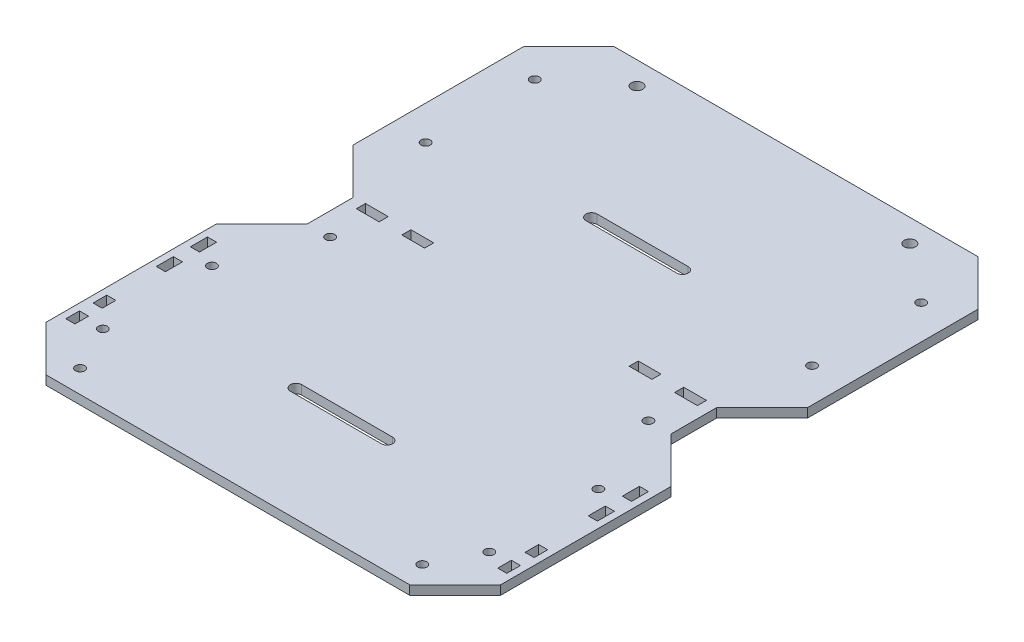
SolidWorks part; units mm, degrees
ref_plane "Front Plane" through (0, 0, 0) normal (0, 0, 1) x (1, 0, 0)
ref_plane "Top Plane" through (0, 0, 0) normal (0, 1, 0) x (1, 0, 0)
ref_plane "Right Plane" through (0, 0, 0) normal (1, 0, 0) x (0, 0, -1)
sketch "Sketch1" plane through (0, 0, 0) normal (0, 1, 0) x (1, 0, 0)
  line L0 (0, -190.8443) -> (0, 164.7825) construction
  line L1 (20, -75.5426) -> (-20, -75.5426) construction
  line L2 (20, -78.0426) -> (-20, -78.0426)
  line L3 (20, -73.0426) -> (-20, -73.0426)
  line L4 (-164.6479, -0.5426) -> (181.8685, -0.5426) construction
  line L5 (145.0227, -10.5426) -> (-122.4663, -10.5426) construction
  line L6 (-80, -10.5426) -> (-80, 9.4574)
  line L7 (-45, 9.4574) -> (-80, 9.4574) construction
  line L8 (20, 54.4574) -> (-20, 54.4574) construction
  line L9 (20, 56.9574) -> (-20, 56.9574)
  line L10 (20, 51.9574) -> (-20, 51.9574)
  line L15 (80, -10.5426) -> (80, 9.4574)
  line L17 (80, -125.5426) -> (-80, -125.5426)
  line L19 (100, -105.5426) -> (100, -30.5426)
  line L20 (100, -105.5426) -> (80, -125.5426)
  line L21 (80, -10.5426) -> (100, -30.5426)
  line L22 (-80, -10.5426) -> (-100, -30.5426)
  line L23 (-100, -105.5426) -> (-80, -125.5426)
  line L24 (-100, -105.5426) -> (-100, -30.5426)
  line L34 (80, 124.4574) -> (-80, 124.4574)
  line L36 (100, 104.4574) -> (80, 124.4574)
  line L37 (100, 104.4574) -> (100, 29.4574)
  line L39 (80, 9.4574) -> (100, 29.4574)
  line L42 (-80, 9.4574) -> (-100, 29.4574)
  line L44 (97, -37.5) -> (97, -45)
  line L45 (97, -93.8222) -> (97, -99.8222)
  line L46 (75, 10) -> (65, 10)
  line L47 (93, -45) -> (93, -37.5)
  line L48 (97, -52.5) -> (97, -60)
  line L49 (97, -37.5) -> (93, -37.5)
  line L50 (97, -45) -> (93, -45)
  line L51 (97, -99.8222) -> (93, -99.8222)
  line L52 (93, -52.5) -> (97, -52.5)
  line L53 (97, -60) -> (93, -60)
  line L54 (93, -99.8222) -> (93, -93.8222)
  line L55 (93, -93.8222) -> (97, -93.8222)
  line L56 (55, 6) -> (45, 6)
  line L57 (97, -87.8222) -> (93, -87.8222)
  line L58 (93, -87.8222) -> (93, -81.8222)
  line L59 (93, -81.8222) -> (97, -81.8222)
  line L60 (93, -60) -> (93, -52.5)
  line L61 (97, -81.8222) -> (97, -87.8222)
  line L62 (-93, -99.8222) -> (-93, -93.8222)
  line L63 (-97, -99.8222) -> (-93, -99.8222)
  line L64 (-97, -93.8222) -> (-97, -99.8222)
  line L65 (-93, -93.8222) -> (-97, -93.8222)
  line L66 (-93, -87.8222) -> (-93, -81.8222)
  line L67 (-97, -87.8222) -> (-93, -87.8222)
  line L68 (-97, -81.8222) -> (-97, -87.8222)
  line L69 (-93, -81.8222) -> (-97, -81.8222)
  line L70 (-97, -60) -> (-93, -60)
  line L71 (-93, -60) -> (-93, -52.5)
  line L72 (-97, -52.5) -> (-97, -60)
  line L73 (-93, -52.5) -> (-97, -52.5)
  line L74 (-97, -45) -> (-93, -45)
  line L75 (-93, -45) -> (-93, -37.5)
  line L76 (-97, -37.5) -> (-93, -37.5)
  line L77 (-97, -37.5) -> (-97, -45)
  line L78 (-45, 6) -> (-55, 6)
  line L79 (75, 10) -> (75, 6)
  line L80 (65, 10) -> (65, 6)
  line L81 (55, 6) -> (55, 10)
  line L82 (45, 10) -> (45, 6)
  line L83 (55, 10) -> (45, 10)
  line L84 (-65, 6) -> (-75, 6)
  line L85 (-75, 10) -> (-75, 6)
  line L86 (-75, 10) -> (-65, 10)
  line L87 (-65, 10) -> (-65, 6)
  line L88 (-55, 6) -> (-55, 10)
  line L89 (-100, 104.4574) -> (-100, 29.4574)
  line L90 (-45, 10) -> (-45, 6)
  line L91 (-55, 10) -> (-45, 10)
  line L92 (75, 6) -> (65, 6)
  line L94 (-100, 104.4574) -> (-80, 124.4574)
  circle A0 centre (85, 94.4574) radius 2
  circle A1 centre (85, 46.4574) radius 2
  circle A2 centre (85, -95.5426) radius 2
  circle A3 centre (85, -47.5426) radius 2
  circle A4 centre (-85, 94.4574) radius 2
  circle A5 centre (-85, 46.4574) radius 2
  circle A6 centre (-85, -47.5426) radius 2
  circle A7 centre (-85, -95.5426) radius 2
  arc A8 (20, -78.0426) -> (20, -73.0426) centre (20, -75.5426) ccw
  arc A9 (-20, -73.0426) -> (-20, -78.0426) centre (-20, -75.5426) ccw
  arc A10 (20, 56.9574) -> (20, 51.9574) centre (20, 54.4574) cw
  arc A11 (-20, 51.9574) -> (-20, 56.9574) centre (-20, 54.4574) cw
  circle A12 centre (60, 114.4574) radius 2.5
  circle A13 centre (-60, 114.4574) radius 2.5
  circle A16 centre (-75, -115.5426) radius 2
  circle A17 centre (-70, -10.5426) radius 2
  circle A18 centre (75, -115) radius 2
  circle A19 centre (70, -10.5426) radius 2
  point P7 (85, -47.5426)
  point P24 (0, -75.5426)
  point P33 (0, 49.4574)
  point P37 (0, 54.4574)
  point P53 (80, -0.5426)
  point P55 (-80, -0.5426)
  point P59 (50, -70.5426)
  point P66 (-50, -70.5426)
  point P82 (-30, 30)
  point P83 (30, 30)
  point P85 (30, -50)
  point P86 (-30, -50)
  point P94 (-30, 30)
  point P116 (95, -87.8222)
  dimension "D8" = 75
  dimension "D9" = 10
  dimension "D22" = 4
  dimension "D24" = 5
  dimension "D26" = 10
  dimension "D5" = 48
  dimension "D6" = 4
  dimension "D10" = 10
  dimension "D1" = 15
  dimension "D4" = 30
  dimension "D7" = 100
  dimension "D11" = 60
  dimension "D23" = 125
  dimension "D25" = 5
  dimension "D27" = 10
  dimension "D28" = 3
  dimension "D29" = 5
  dimension "D31" = 7.5
  dimension "D32" = 7.5
  dimension "D33" = 7.5
  dimension "D34" = 6
  dimension "D35" = 6
  dimension "D36" = 6
  dimension "D37" = 10
  dimension "D38" = 10
extrude "Boss-Extrude1" add sketch "Sketch1" along normal blind 4
